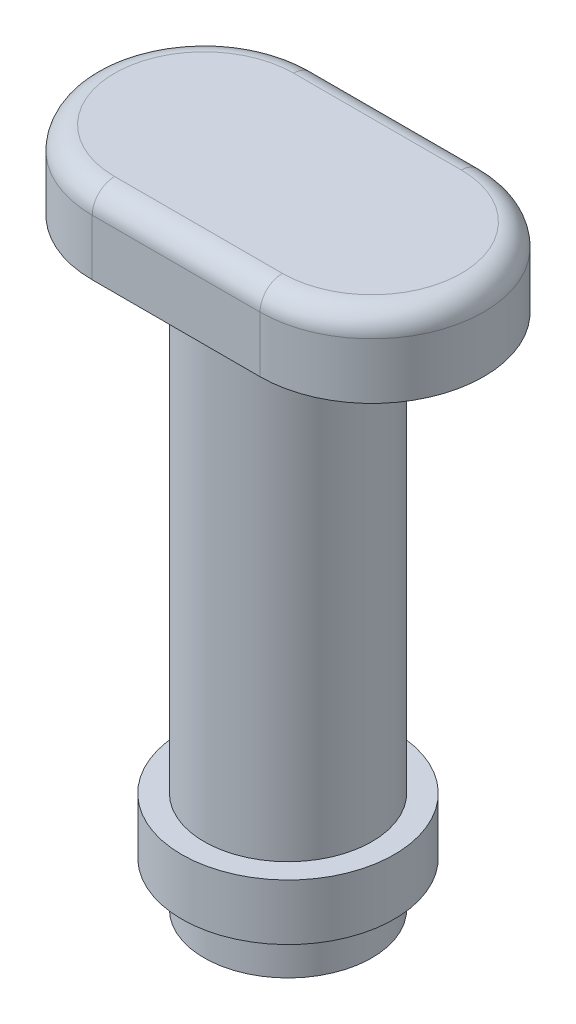
SolidWorks part; units mm, degrees
material "ABS"
ref_plane "Front Plane" through (0, 0, 0) normal (0, 0, 1) x (1, 0, 0)
ref_plane "Top Plane" through (0, 0, 0) normal (0, 1, 0) x (1, 0, 0)
ref_plane "Right Plane" through (0, 0, 0) normal (1, 0, 0) x (0, 0, -1)
sketch "Sketch1" plane through (0, 0, 0) normal (0, 1, 0) x (1, 0, 0)
  line L0 (-1.5, 0) -> (1.5, 0) construction
  line L1 (-1.5, 2) -> (1.5, 2)
  line L2 (-1.5, -2) -> (1.5, -2)
  arc A0 (-1.5, 2) -> (-1.5, -2) centre (-1.5, 0) ccw
  arc A1 (1.5, -2) -> (1.5, 2) centre (1.5, 0) ccw
  point P2 (0, 0)
  dimension "D1" = 2
  dimension "D2" = 3
extrude "Boss-Extrude1" add sketch "Sketch1" along normal blind 1.4
sketch "Sketch2" plane through (0, 0, 0) normal (0, -1, 0) x (-1, 0, 0)
  circle A0 centre (0, 0) radius 1.5
  dimension "D1" = 3
extrude "Boss-Extrude2" add sketch "Sketch2" along normal blind 10
ref_plane "Plane1" through (0, -9.2, 0) normal (0, -1, 0) x (-1, 0, 0)
sketch "Sketch3" plane through (0, -9.2, 0) normal (0, -1, 0) x (-1, 0, 0)
  circle A0 centre (0, 0) radius 1.9
  dimension "D1" = 3.8
extrude "Boss-Extrude3" add sketch "Sketch3" against normal blind 1
fillet "Fillet1" radius 0.4 4 edges at (0, 1.4, -2) (3.5, 1.4, 0) (0, 1.4, 2) (-3.5, 1.4, 0)
